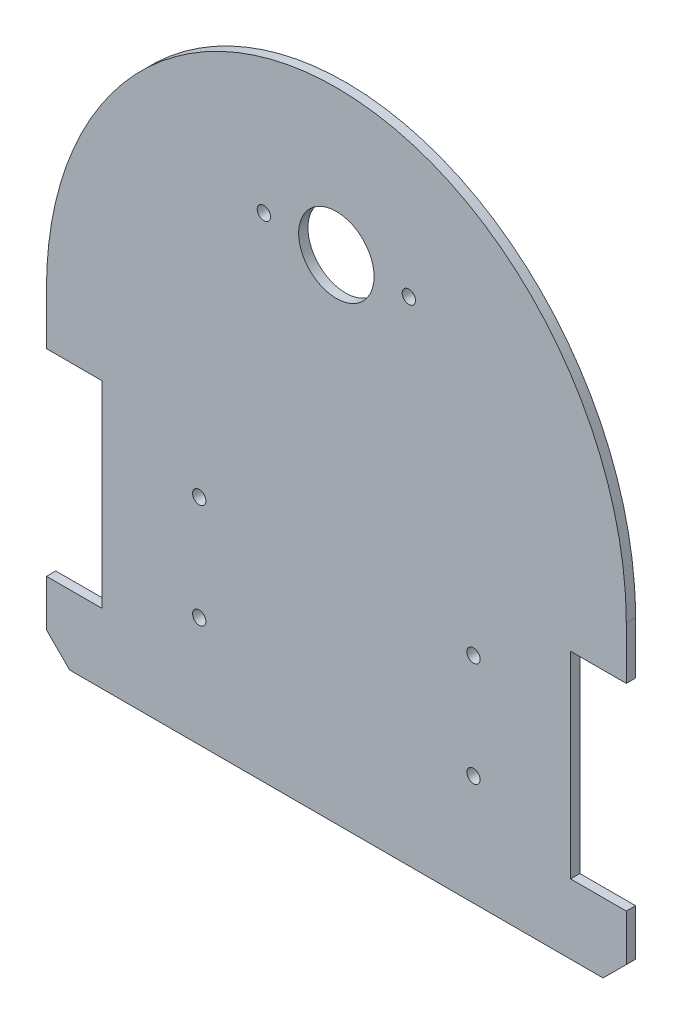
SolidWorks part; units mm, degrees
material "A-Glass Fiber"
ref_plane "Top Plane" through (0, 0, 0) normal (0, 0, 1) x (1, 0, 0)
ref_plane "Right Plane" through (0, 0, 0) normal (0, 1, 0) x (1, 0, 0)
ref_plane "Front Plane" through (0, 0, 0) normal (1, 0, 0) x (0, 0, -1)
sketch "Sketch1" plane through (0, 0, 0) normal (0, 0, 1) x (1, 0, 0)
  line L1 (50, -55) -> (-50, -55)
  line L2 (50, -55) -> (50, 55)
  line L3 (50, 55) -> (-50, 55)
  line L4 (-50, -55) -> (-50, 55)
  line L5 (50, -55) -> (-50, 55) construction
  line L6 (50, 55) -> (-50, -55) construction
  point P0 (0, 0)
  dimension "D1" = 100
  dimension "D2" = 110
extrude "Boss-Extrude1" add sketch "Sketch1" along normal blind 1.6
sketch "Sketch2" plane through (0, 0, 1.6) normal (0, 0, 1) x (1, 0, 0)
  line L0 (-50, 55) -> (-50, -55) construction
  line L1 (50, 55) -> (-50, 55) construction
  line L6 (-50, 0) -> (-70, 0)
  line L7 (-70, 0) -> (-70, 70)
  line L8 (50, -55) -> (50, 55) construction
  line L9 (-70, 70) -> (70, 70)
  line L10 (70, 70) -> (70, 0)
  line L11 (70, 0) -> (50, 0)
  ellipse E0 centre (0, 0) end of major axis (0, -55) minor radius 50 (50, 0) -> (-50, 0) ccw
  point P14 (0, 70)
  dimension "D1" = 140
  dimension "D2" = 70
extrude "Cut-Extrude1" cut sketch "Sketch2" against normal through all
sketch "Sketch3" plane through (0, 0, 1.6) normal (0, 0, 1) x (1, 0, 0)
  line L1 (-50, -9) -> (-40.4, -9)
  line L2 (-50, -9) -> (-50, -43)
  line L3 (-50, -43) -> (-40.4, -43)
  line L4 (-40.4, -9) -> (-40.4, -43)
  line L6 (0, -0.88) -> (0, 0.88) construction
  line L7 (50, -9) -> (40.4, -9)
  line L8 (50, -43) -> (40.4, -43)
  line L9 (40.4, -9) -> (40.4, -43)
  line L10 (50, -9) -> (50, -43)
  line L11 (-50, 0) -> (-50, -55) construction
  line L13 (-50, -55) -> (50, -55) construction
  point P4 (-48.6085, -21)
  dimension "D1" = 9.6
  dimension "D2" = 34
  dimension "D3" = 12
extrude "Cut-Extrude2" cut sketch "Sketch3" against normal through all
chamfer "Chamfer1" distance 4 angle 45 2 edges at (50, -55, 0.8) (-50, -55, 0.8)
sketch "Sketch4" plane through (0, 0, 1.6) normal (0, 0, 1) x (1, 0, 0)
  line L0 (-46, -55) -> (46, -55) construction
  circle A0 centre (0, 30) radius 6.5
  point P2 (3.3411, 29.8134)
  dimension "D1" = 13
  dimension "D2" = 85
extrude "Cut-Extrude3" cut sketch "Sketch4" against normal through all
sketch "Sketch5" plane through (0, 0, 1.6) normal (0, 0, 1) x (1, 0, 0)
  line L0 (-50, -43) -> (-40.4, -43) construction
  line L3 (0, -0.88) -> (0, 0.88) construction
  circle A0 centre (-23.65, -18) radius 1.15
  circle A1 centre (-23.65, -36) radius 1.15
  circle A2 centre (23.65, -36) radius 1.15
  circle A3 centre (23.65, -18) radius 1.15
  point P7 (-23.65, -36)
  dimension "D3" = 2.3
  dimension "D1" = 7
  dimension "D2" = 18
extrude "Cut-Extrude4" cut sketch "Sketch5" against normal through all
sketch "Sketch6" plane through (0, 0, 1.6) normal (0, 0, 1) x (1, 0, 0)
  line L0 (-12.5, 30) -> (12.5, 30) construction
  circle A1 centre (-12.5, 30) radius 1.15
  circle A2 centre (12.5, 30) radius 1.15
  point P2 (0, 0)
  point P7 (0, 0)
  point P8 (0, 0)
  dimension "D2" = 2.3
  dimension "D1" = 25
extrude "Cut-Extrude5" cut sketch "Sketch6" against normal through all
equation "\"pozicija motora\" = 12mm"
equation "\"D3@Sketch3\"=\"pozicija motora\""
equation "\"pozicija castera\" = 85mm"
equation "\"D2@Sketch4\"=\"pozicija castera\""
